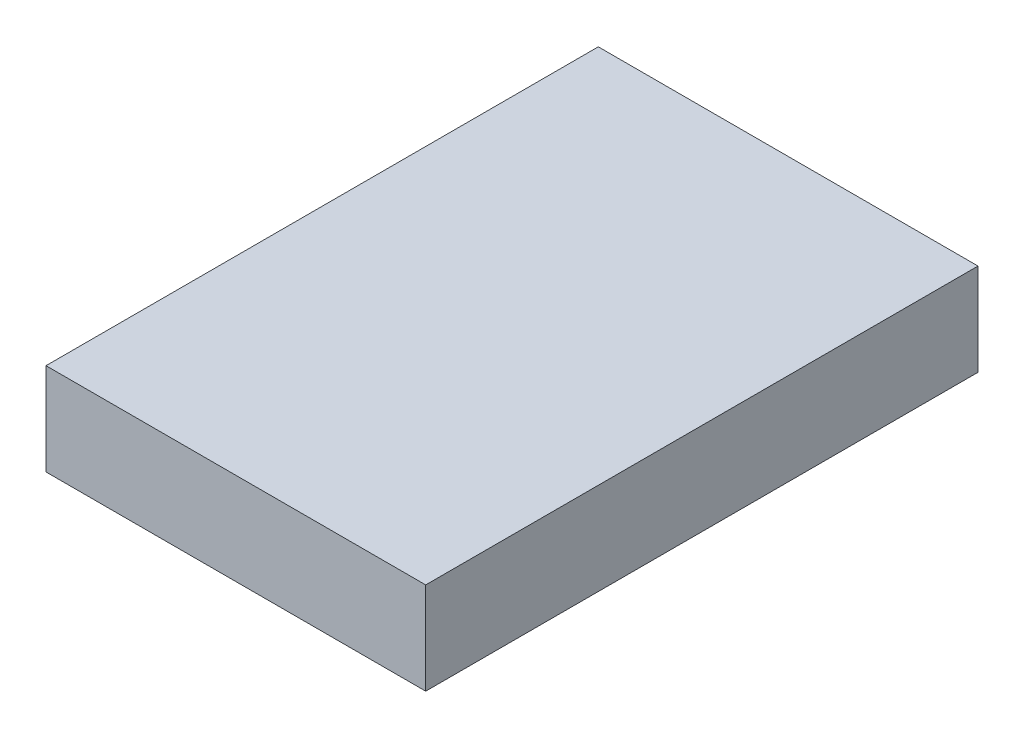
SolidWorks part; units mm, degrees
ref_plane "Front Plane" through (0, 0, 0) normal (0, 0, 1) x (1, 0, 0)
ref_plane "Top Plane" through (0, 0, 0) normal (0, 1, 0) x (1, 0, 0)
ref_plane "Right Plane" through (0, 0, 0) normal (1, 0, 0) x (0, 0, -1)
sketch "Sketch1" plane through (0, 0, 0) normal (0, 1, 0) x (1, 0, 0)
  line L1 (-8.25, 12) -> (8.25, 12)
  line L2 (-8.25, 12) -> (-8.25, -12)
  line L3 (-8.25, -12) -> (8.25, -12)
  line L4 (8.25, 12) -> (8.25, -12)
  line L5 (-8.25, 12) -> (8.25, -12) construction
  line L6 (-8.25, -12) -> (8.25, 12) construction
  point P0 (0, 0)
  dimension "D1" = 16.5
  dimension "D2" = 24
extrude "Boss-Extrude1" add sketch "Sketch1" along normal blind 4
sketch "Sketch2" plane through (0, 4, 0) normal (0, 1, 0) x (1, 0, 0)
  point P0 (0, 0)
